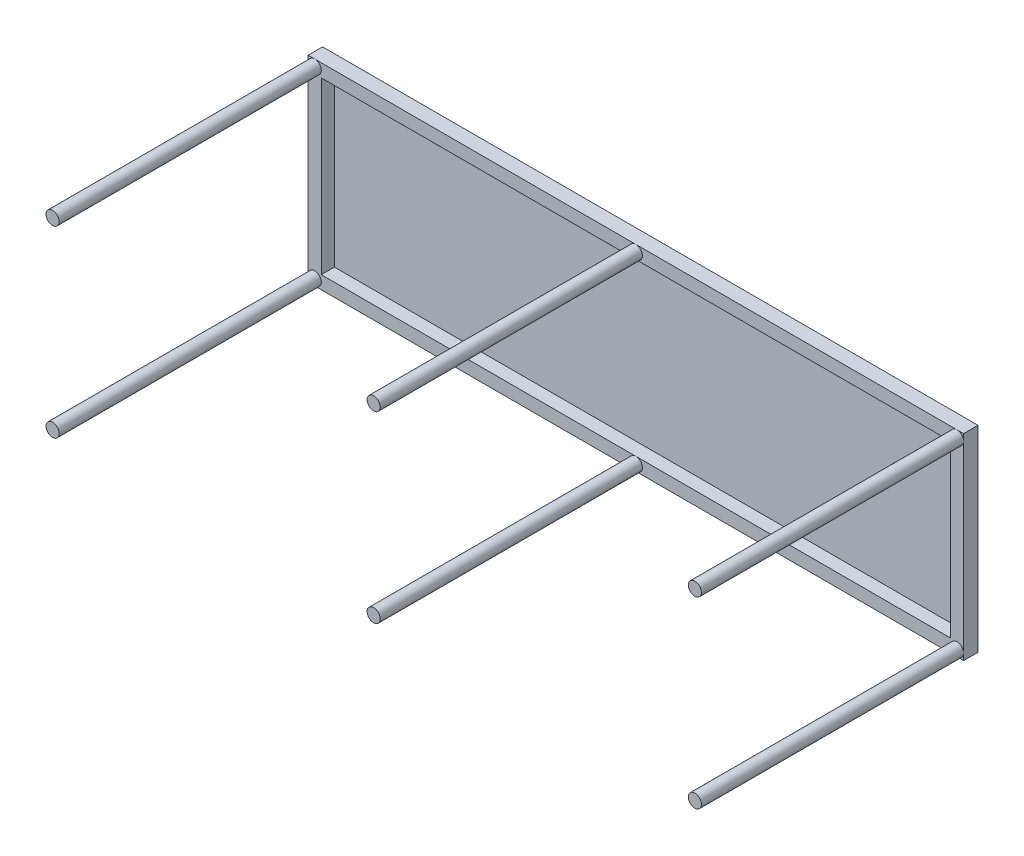
SolidWorks part; units mm, degrees
ref_plane "前视基准面" through (0, 0, 0) normal (0, 0, 1) x (1, 0, 0)
ref_plane "上视基准面" through (0, 0, 0) normal (0, 1, 0) x (1, 0, 0)
ref_plane "右视基准面" through (0, 0, 0) normal (1, 0, 0) x (0, 0, -1)
sketch "草图1" plane through (0, 0, 0) normal (0, 0, 1) x (1, 0, 0)
  line L1 (-59.0364, 27.2158) -> (4940.9636, 27.2158)
  line L2 (-59.0364, 27.2158) -> (-59.0364, -1472.7842)
  line L3 (-59.0364, -1472.7842) -> (4940.9636, -1472.7842)
  line L4 (4940.9636, 27.2158) -> (4940.9636, -1472.7842)
  dimension "D1" = 5000
  dimension "D2" = 1500
extrude "凸台-拉伸1" add sketch "草图1" along normal blind 10
sketch "草图2" plane through (0, 0, 10) normal (0, 0, 1) x (1, 0, 0)
  line L0 (40.9636, -72.7842) -> (4840.9636, -72.7842)
  line L1 (-59.0364, 27.2158) -> (4940.9636, 27.2158)
  line L2 (-59.0364, 27.2158) -> (-59.0364, -1472.7842)
  line L3 (-59.0364, -1472.7842) -> (4940.9636, -1472.7842)
  line L4 (4940.9636, 27.2158) -> (4940.9636, -1472.7842)
  line L5 (4840.9636, -72.7842) -> (4840.9636, -1372.7842)
  line L6 (40.9636, -1372.7842) -> (4840.9636, -1372.7842)
  line L7 (40.9636, -72.7842) -> (40.9636, -1372.7842)
  dimension "D1" = 100
extrude "凸台-拉伸2" add sketch "草图2" along normal blind 100
sketch "草图3" plane through (0, 0, 110) normal (0, 0, 1) x (1, 0, 0)
  circle A0 centre (-9.0364, -22.7842) radius 50
  circle A1 centre (-9.0364, -1422.7842) radius 50
  circle A2 centre (4890.9636, -1422.7842) radius 50
  circle A3 centre (4890.9636, -22.7842) radius 50
extrude "凸台-拉伸3" add sketch "草图3" along normal blind 2000
sketch "草图4" plane through (0, 0, 110) normal (0, 0, 1) x (1, 0, 0)
  circle A0 centre (2440.9636, -22.7842) radius 50
  circle A1 centre (2440.9636, -1422.7842) radius 50
extrude "凸台-拉伸4" add sketch "草图4" along normal up to surface (2000 mm away) up to face at (40.9636, -1422.7842, 2110)
